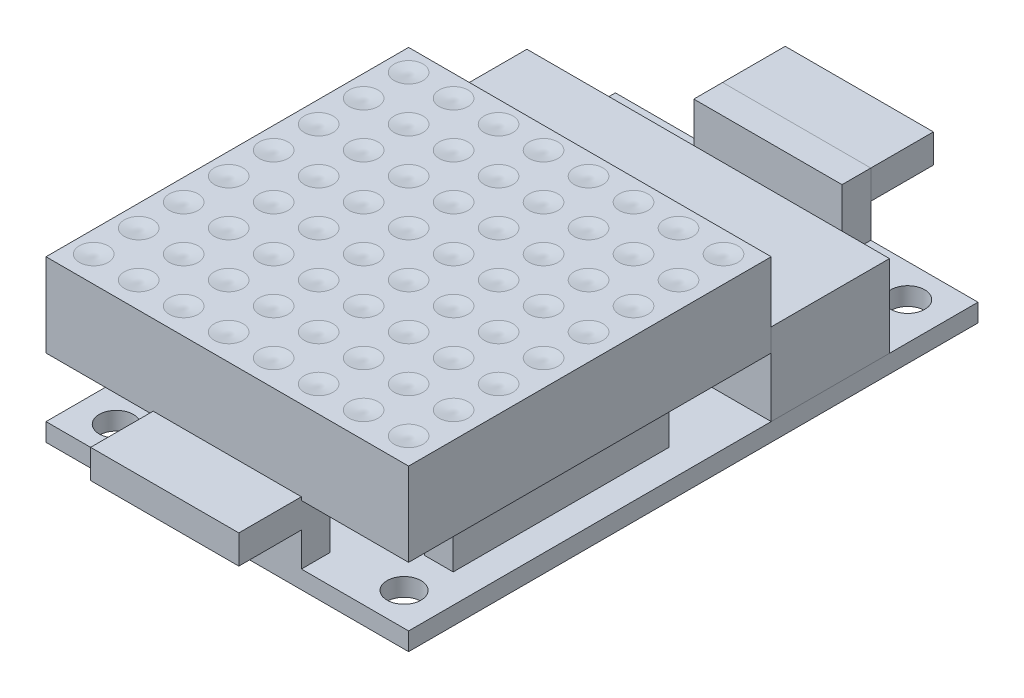
SolidWorks part; units mm, degrees
ref_plane "Front Plane" through (0, 0, 0) normal (0, 0, 1) x (1, 0, 0)
ref_plane "Top Plane" through (0, 0, 0) normal (0, 1, 0) x (1, 0, 0)
ref_plane "Right Plane" through (0, 0, 0) normal (1, 0, 0) x (0, 0, -1)
sketch "Sketch1" plane through (0, 0, 0) normal (0, 1, 0) x (1, 0, 0)
  line L1 (0, 0) -> (32, 0)
  line L2 (0, 0) -> (0, 32)
  line L3 (0, 32) -> (32, 32)
  line L4 (32, 0) -> (32, 32)
  dimension "D1" = 32
  dimension "D2" = 32
extrude "Boss-Extrude1" add sketch "Sketch1" along normal blind 7.36
sketch "Sketch2" plane through (0, 0, 0) normal (0, -1, 0) x (1, 0, 0)
  line L0 (0, -32) -> (0, 0) construction
  line L1 (29.46, -25.525) -> (26.92, -25.525)
  line L2 (29.46, -25.525) -> (29.46, -6.475)
  line L3 (29.46, -6.475) -> (26.92, -6.475)
  line L4 (26.92, -25.525) -> (26.92, -6.475)
  line L5 (5.08, -25.525) -> (2.54, -25.525)
  line L6 (5.08, -25.525) -> (5.08, -6.475)
  line L7 (5.08, -6.475) -> (2.54, -6.475)
  line L8 (2.54, -25.525) -> (2.54, -6.475)
  line L9 (32, 0) -> (32, -32) construction
  line L10 (32, -16) -> (0, -16) construction
  point P14 (5.08, -16)
  point P15 (26.92, -16)
  dimension "D1" = 2.54
  dimension "D2" = 2.54
  dimension "D3" = 2.54
  dimension "D4" = 2.54
  dimension "D5" = 19.05
  dimension "D6" = 19.05
extrude "Boss-Extrude2" add sketch "Sketch2" along normal blind 5.2386
sketch "Sketch3" plane through (0, -5.2386, 0) normal (0, -1, 0) x (1, 0, 0)
  line L0 (32, 0) -> (32, -32) construction
  line L1 (0, 0) -> (32, 0)
  line L2 (0, 0) -> (0, -50.25)
  line L3 (0, -50.25) -> (32, -50.25)
  line L4 (32, 0) -> (32, -50.25)
  dimension "D1" = 50.25
extrude "Boss-Extrude3" add sketch "Sketch3" along normal blind 1.5875
sketch "Sketch4" plane through (0, -6.8261, 0) normal (0, -1, 0) x (1, 0, 0)
  line L0 (28.7, -47.35) -> (32, -47.35) construction
  line L1 (32, -50.25) -> (32, 0) construction
  line L2 (28.7, -47.35) -> (28.7, -50.25) construction
  line L4 (0, -50.25) -> (32, -50.25) construction
  line L5 (3.3, -47.35) -> (0, -47.35) construction
  line L6 (0, 0) -> (0, -50.25) construction
  line L7 (3.3, -47.35) -> (3.3, -50.25) construction
  line L8 (3.3, -2.9) -> (3.3, 0) construction
  line L9 (32, 0) -> (0, 0) construction
  line L10 (3.3, -2.9) -> (0, -2.9) construction
  line L11 (28.7, -2.9) -> (32, -2.9) construction
  line L12 (28.7, -2.9) -> (28.7, 0) construction
  circle A0 centre (3.3, -47.35) radius 1.5
  circle A1 centre (28.7, -47.35) radius 1.5
  circle A2 centre (28.7, -2.9) radius 1.5
  circle A3 centre (3.3, -2.9) radius 1.5
  point P17 (16.2309, -47.2108)
  dimension "D1" = 3
  dimension "D6" = 3
  dimension "D2" = 44.45
  dimension "D3" = 25.4
  dimension "D4" = 44.45
  dimension "D5" = 25.4
extrude "Cut-Extrude1" cut sketch "Sketch4" against normal up to surface (1.5875 mm away) up to face at (3.81, -5.2386, -16)
sketch "Sketch5" plane through (0, 7.36, 0) normal (0, 1, 0) x (1, 0, 0)
  line L0 (32, 32) -> (0, 32) construction
  line L1 (0, 32) -> (0, 0) construction
  circle A0 centre (1.905, 30.095) radius 1.27
  dimension "D1" = 2.54
  dimension "D2" = 1.905
  dimension "D3" = 1.905
extrude "Cut-Extrude2" cut sketch "Sketch5" against normal blind 0.254 draft 80
pattern_linear "LPattern1" count 8 spacing 3.97 along (1, 0, 0) count 8 spacing 3.97 along (0, 0, 1) of "Cut-Extrude2"
sketch "Sketch6" plane through (0, -5.2386, 0) normal (0, 1, 0) x (1, 0, 0)
  line L0 (32, 50.25) -> (32, 0) construction
  line L1 (32, 32) -> (0, 32)
  line L2 (32, 32) -> (32, 42.4395)
  line L3 (32, 42.4395) -> (0, 42.4395)
  line L4 (0, 32) -> (0, 42.4395)
  line L5 (0, 0) -> (0, 50.25) construction
  line L6 (32, 32) -> (0, 32) construction
  line L7 (0, 50.25) -> (32, 50.25) construction
  dimension "D1" = 7.8105
extrude "Boss-Extrude4" add sketch "Sketch6" along normal blind 7.239 separate body
sketch "Sketch7" plane through (0, -5.2386, 0) normal (0, 1, 0) x (1, 0, 0)
  line L0 (0, 50.25) -> (32, 50.25) construction
  line L1 (22.5405, 47.71) -> (9.4595, 47.71)
  line L2 (22.5405, 47.71) -> (22.5405, 50.25)
  line L3 (22.5405, 50.25) -> (9.4595, 50.25)
  line L4 (9.4595, 47.71) -> (9.4595, 50.25)
  point P6 (16, 47.71)
  point P7 (16, 50.25)
  point P8 (16, 50.25)
  dimension "D1" = 2.54
  dimension "D2" = 13.081
extrude "Boss-Extrude5" add sketch "Sketch7" along normal blind 5.5245 separate body
sketch "Sketch8" plane through (0, 0, -50.25) normal (0, 0, -1) x (-1, 0, 0)
  line L0 (-22.5405, 0.2859) -> (-9.4595, 0.2859) construction
  line L1 (-22.5405, 0.2859) -> (-9.4595, 0.2859)
  line L2 (-22.5405, 0.2859) -> (-22.5405, -2.2541)
  line L3 (-22.5405, -2.2541) -> (-9.4595, -2.2541)
  line L4 (-9.4595, 0.2859) -> (-9.4595, -2.2541)
  line L5 (-22.5405, 0.2859) -> (-22.5405, -5.2386) construction
  line L6 (-9.4595, 0.2859) -> (-9.4595, -5.2386) construction
  dimension "D1" = 2.54
extrude "Boss-Extrude6" add sketch "Sketch8" along normal blind 5.5245
ref_plane "Plane1" through (0, 0, -25.125) normal (0, 0, -1) x (-1, 0, 0)
mirror "Mirror1" about plane through (0, 0, -25.125) normal (0, 0, -1) of "Boss-Extrude6", "Boss-Extrude5"
equation "\"led_height\"=0.289764"
equation "\"D1@Boss-Extrude1\"=\"led_height\""
equation "\"D1@Boss-Extrude2\"=.5590 - \"led_height\" - 1.6mm"
